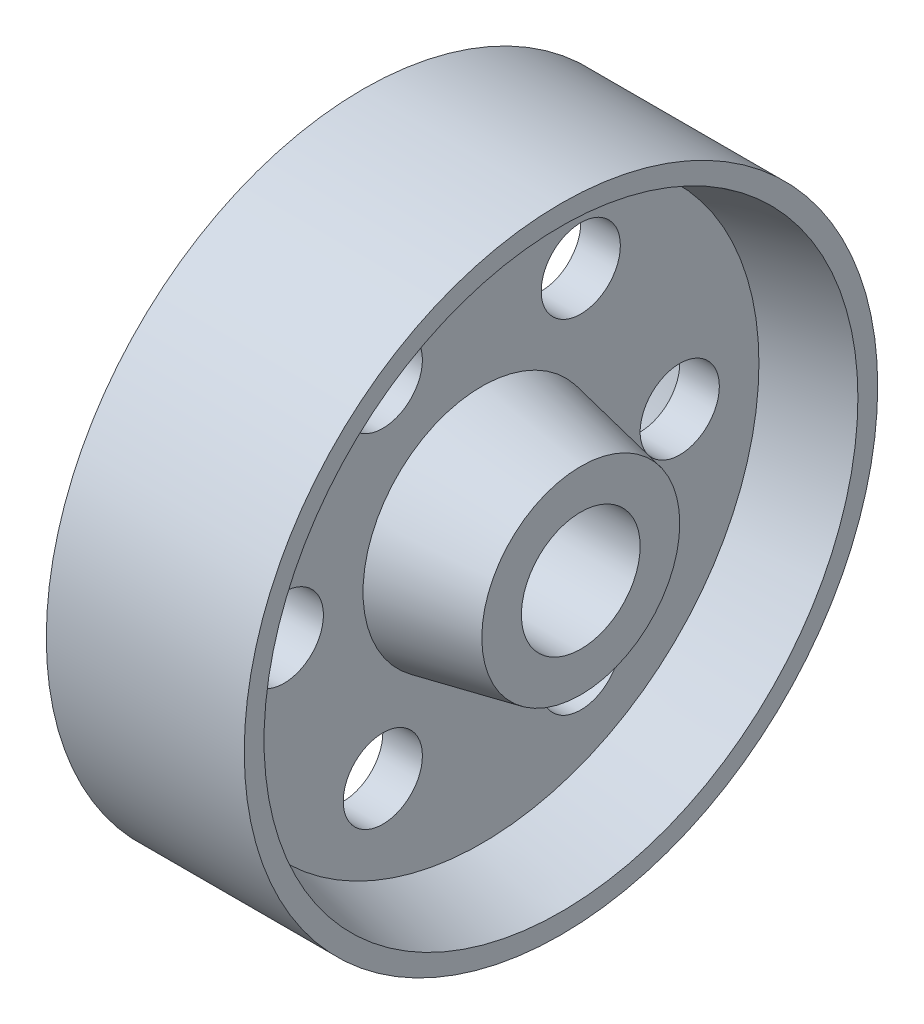
SolidWorks part; units mm, degrees
ref_plane "Front Plane" through (0, 0, 0) normal (1, 0, 0) x (0, 1, 0)
ref_plane "Top Plane" through (0, 0, 0) normal (0, 0, 1) x (0, 1, 0)
ref_plane "Right Plane" through (0, 0, 0) normal (0, 1, 0) x (-1, 0, 0)
sketch "Sketch2" plane through (0, 0, 0) normal (0, 1, 0) x (-1, 0, 0)
  line L0 (0, 0) -> (14.5327, 0)
  line L1 (0, 0) -> (0, 9.525)
  line L2 (0, 9.525) -> (19.05, 9.525)
  line L3 (19.05, 9.525) -> (19.05, 15.875)
  line L4 (19.05, 15.875) -> (3.175, 19.05)
  line L5 (3.175, 19.05) -> (3.175, 44.45)
  line L6 (3.175, 44.45) -> (15.875, 47.625)
  line L7 (15.875, 47.625) -> (15.875, 50.8)
  line L8 (15.875, 50.8) -> (0, 50.8)
  line L9 (0, 50.8) -> (0, 9.525)
  point P10 (5.7602, 40.6042)
  dimension "D1" = 15.875
  dimension "D2" = 19.05
  dimension "D3" = 9.525
  dimension "D4" = 44.45
  dimension "D5" = 47.625
  dimension "D6" = 50.8
  dimension "D7" = 19.05
  dimension "D8" = 15.875
  dimension "D9" = 3.175
revolve "Revolve1" add sketch "Sketch2" angle 360 about L0
sketch "Sketch3" plane through (0, 0, 0) normal (1, 0, 0) x (0, 1, 0)
  circle A0 centre (0, 31.75) radius 6.35
  circle A1 centre (27.4963, 15.875) radius 6.35
  circle A2 centre (27.4963, -15.875) radius 6.35
  circle A3 centre (0, -31.75) radius 6.35
  circle A4 centre (-27.4963, -15.875) radius 6.35
  circle A5 centre (-27.4963, 15.875) radius 6.35
  point P16 (0, 0)
  dimension "D1" = 12.7
  dimension "D2" = 31.75
  dimension "D3" = 6
extrude "Cut-Extrude1" cut sketch "Sketch3" against normal through all
mirror "Mirror1" about plane through (0, 0, 0) normal (-1, 0, 0) of bodies 102
